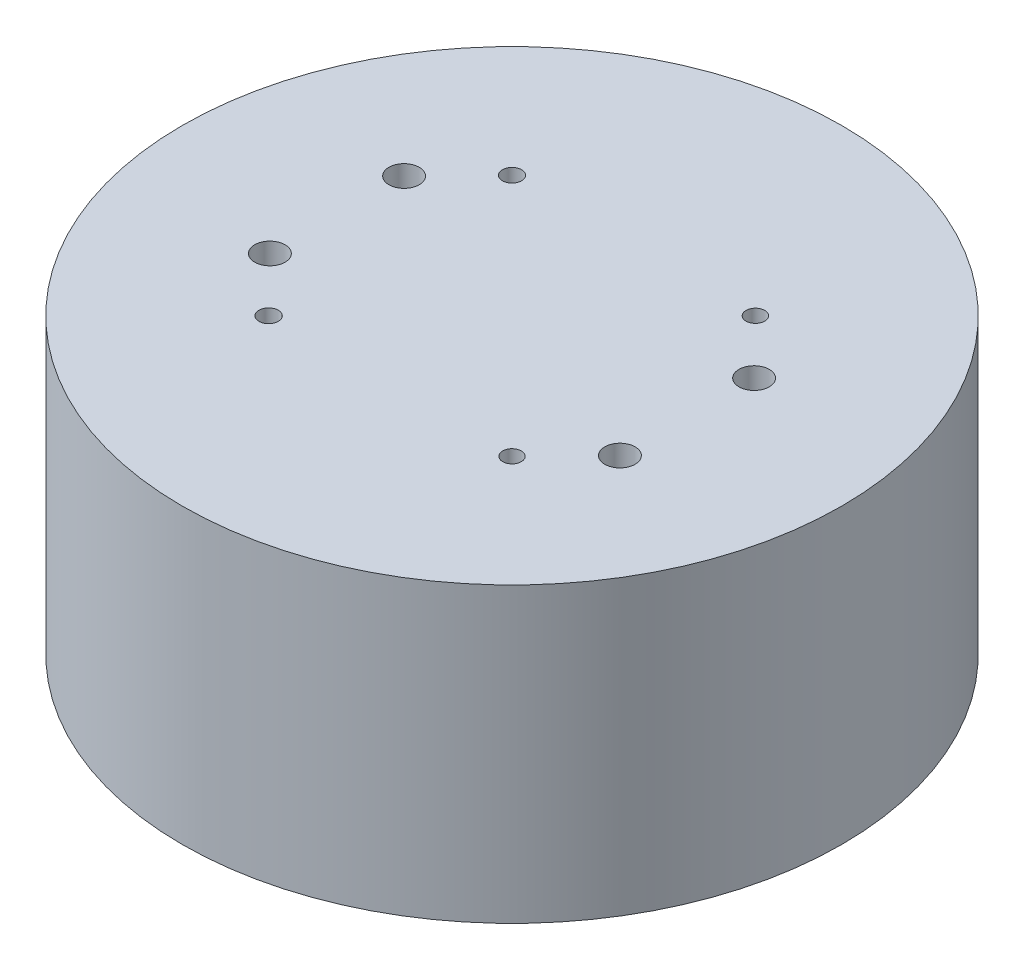
SolidWorks part; units mm, degrees
ref_plane "Front Plane" through (0, 0, 0) normal (0, 0, 1) x (1, 0, 0)
ref_plane "Top Plane" through (0, 0, 0) normal (0, 1, 0) x (1, 0, 0)
ref_plane "Right Plane" through (0, 0, 0) normal (1, 0, 0) x (0, 0, -1)
sketch "Sketch2" plane through (0, 0, 0) normal (0, 1, 0) x (1, 0, 0)
  line L0 (0, 0) -> (0, 56.515)
  circle A0 centre (0, 0) radius 51.435
  circle A1 centre (0, 0) radius 56.515
  circle A2 centre (0, 0) radius 47.2017
  circle A3 centre (0, 0) radius 42.1217
  dimension "D1" = 14.3933
  dimension "D2" = 5.08
  dimension "D3" = 4.2333
  dimension "D4" = 5.08
  dimension "D5" = 102.87
  dimension "D6" = 94.4033
extrude "Boss-Extrude1" add sketch "Sketch2" along normal blind 35 contours A1 A0 | A2 A3
sketch "Sketch3" plane through (0, 35, 0) normal (0, 1, 0) x (1, 0, 0)
  circle A0 centre (0, 0) radius 56.515
  dimension "D1" = 113.03
extrude "Boss-Extrude2" add sketch "Sketch3" along normal blind 15.24
sketch "Sketch4" plane through (0, 50.24, 0) normal (0, 1, 0) x (1, 0, 0)
  line L0 (0, 37.845) -> (0, -37.845) construction
  line L1 (37.845, 0) -> (-37.845, 0) construction
  line L2 (26.7605, 26.7605) -> (-26.7605, -26.7605) construction
  line L3 (-26.7605, 26.7605) -> (26.7605, -26.7605) construction
  circle A0 centre (0, 0) radius 37.845 construction
  circle A1 centre (0, 0) radius 29.5 construction
  circle A2 centre (20.8597, 20.8597) radius 1.6
  circle A3 centre (20.8597, -20.8597) radius 1.6
  circle A4 centre (-20.8597, -20.8597) radius 1.6588
  circle A5 centre (-20.8597, 20.8597) radius 1.651
  point P7 (0, 0)
  point P10 (0, 0)
  point P13 (0, 0)
  point P16 (0, 0)
  dimension "D1" = 75.69
  dimension "D2" = 59
  dimension "D3" = 45
  dimension "D4" = 45
  dimension "D5" = 3.2
  dimension "D6" = 3.2
  dimension "D7" = 3.3175
  dimension "D8" = 3.302
extrude "Cut-Extrude1" cut sketch "Sketch4" against normal through all both and the other way through all
sketch "Sketch5" plane through (0, 0, 0) normal (0, -1, 0) x (-1, 0, 0)
  line L0 (0, 0) -> (0, 29.5)
  line L1 (13.9476, 25) -> (-13.9476, 25)
  circle A1 centre (0, 0) radius 37.845
  circle A2 centre (0, 0) radius 29.5
  arc A3 (-13.9476, 54.7669) -> (13.9476, 54.7669) centre (0, 0) cw
  circle A4 centre (0, 0) radius 56.515 construction
  point P9 (0, 25)
  dimension "D1" = 75.69
  dimension "D2" = 59
  dimension "D3" = 25
  dimension "D4" = 31.515
ref_plane "Plane1" through (0, 0, -56.515) normal (0, 0, 1) x (1, 0, 0)
sketch "Sketch6" plane through (0, 50.24, 0) normal (0, 1, 0) x (1, 0, 0)
  line L0 (0, 0) -> (0, 56.515) construction
  line L1 (0, 0) -> (0, -56.515) construction
  line L2 (-56.515, 0) -> (56.515, 0) construction
  circle A0 centre (0, 0) radius 56.515 construction
  circle A1 centre (0, 30.48) radius 2.6
  circle A2 centre (0, -30.48) radius 2.6
  point P10 (0, 0)
  dimension "D2" = 5.2
  dimension "D3" = 5.2
  dimension "D1" = 113.03
  dimension "D4" = 30.48
  dimension "D5" = 30.48
ref_plane "Plane3" through (0, 0, -47.244) normal (0, 0, 1) x (1, 0, 0)
ref_plane "Plane4" through (17.78, 0, 0) normal (1, 0, 0) x (0, 0, -1)
sketch "Sketch13" plane through (0, 0, -56.515) normal (0, 0, 1) x (1, 0, 0)
  line L0 (0, 0) -> (0, 32.5704) construction
sketch "Sketch14" plane through (0, 0, -56.515) normal (0, 0, 1) x (1, 0, 0)
  line L0 (0, 0) -> (0, 50.24) construction
  line L1 (-56.515, 0) -> (56.515, 0) construction
  line L2 (56.515, 50.24) -> (-56.515, 50.24) construction
  line L3 (0, 20) -> (-5.7214, 20) construction
  line L4 (0, 0) -> (0, 25)
  circle A0 centre (0, 15) radius 10
  dimension "D3" = 20
  dimension "D1" = 10
  dimension "D2" = 25
sketch "Sketch20" plane through (0, 0, 0) normal (0, -1, 0) x (-1, 0, 0)
  circle A0 centre (0, 0) radius 56.515
sketch "Sketch32" plane through (0, 50.24, 0) normal (0, 1, 0) x (1, 0, 0)
  line L0 (0, 56.515) -> (0, -56.515) construction
  line L1 (-56.515, 0) -> (56.515, 0) construction
  line L2 (-30, 0.5) -> (-30, 0) construction
  line L5 (30, 11.5) -> (30, -11.5) construction
  line L6 (-30, 11.5) -> (-30, -11.5) construction
  line L7 (30, 0.5) -> (30, 0) construction
  circle A0 centre (0, 0) radius 56.515 construction
  circle A6 centre (30, 11.5) radius 2.6
  circle A7 centre (30, -11.5) radius 2.6
  circle A8 centre (-30, -11.5) radius 2.6
  circle A9 centre (-30, 11.5) radius 2.6
  point P9 (-28.7356, -11.5)
  point P11 (30, 0)
  point P23 (28.7356, -11.5)
  dimension "D1" = 30
  dimension "D2" = 23
extrude "Cut-Extrude18" cut sketch "Sketch32" against normal up to next
sketch "草图1" plane through (0, 35, 0) normal (0, -1, 0) x (-1, 0, 0)
  circle A0 centre (30, 11.5) radius 6
  circle A1 centre (30, -11.5) radius 6
  circle A2 centre (-30, 11.5) radius 6
  circle A3 centre (-30, -11.5) radius 6
extrude "切除-拉伸1" cut sketch "草图1" against normal blind 5
sketch "草图3" plane through (0, 0, -56.515) normal (0, 0, 1) x (1, 0, 0)
  line L0 (0, 0) -> (0, 35) construction
  circle A0 centre (0, 25) radius 10
  point P5 (0, 0)
  dimension "D1" = 20
  dimension "D2" = 35
  dimension "D3" = 10
extrude "切除-拉伸2" cut sketch "草图3" along normal up to surface (15.5976 mm away)
sketch "草图4" plane through (0, 0, -56.515) normal (0, 0, 1) x (1, 0, 0)
  circle A0 centre (0, 25) radius 10
extrude "拉伸-薄壁1" add sketch "草图4" along normal up to surface (17.1547 mm away) thin
sketch "草图6" plane through (0, 0, -56.515) normal (0, 0, 1) x (1, 0, 0)
  line L0 (-6.6399, 0) -> (6.6399, 0)
  arc A0 (6.6399, 0) -> (-6.6399, 0) centre (0, 25) cw
ref_plane "基准面1" through (13, 0, 0) normal (1, 0, 0) x (0, 0, -1)
ref_plane "基准面2" through (0, 7, 0) normal (0, 1, 0) x (1, 0, 0)
sketch "草图10" plane through (0, 7, 0) normal (0, 1, 0) x (1, 0, 0)
  line L0 (0, 47.2017) -> (0, 51.435)
  line L4 (-15, 44.7549) -> (-15, 49.1992)
  line L5 (-15, 49.1992) -> (-15, 44.7549) construction
  line L10 (15, 44.7549) -> (15, 49.1992)
  circle A0 centre (0, 0) radius 47.2017 construction
  arc A3 (-11.1803, 50.2052) -> (11.1803, 50.2052) centre (0, 0) ccw construction
  arc A4 (15.0893, 49.1719) -> (-15.0893, 49.1719) centre (0, 0) ccw
  arc A5 (15.1117, 44.7173) -> (-15.1117, 44.7173) centre (0, 0) ccw
  dimension "D1" = 0
extrude "拉伸-薄壁3" add sketch "草图10" along normal up to surface (28 mm away) thin
sketch "草图11" plane through (0, 0, 0) normal (0, -1, 0) x (-1, 0, 0)
  circle A0 centre (0, 0) radius 56.515
extrude "切除-拉伸-薄壁3" cut sketch "草图11" against normal up to next thin
sketch "草图12" plane through (0, 7, 0) normal (0, 1, 0) x (1, 0, 0)
  line L0 (15.1244, 44.7549) -> (20, 44.7549)
  line L1 (20, 44.7549) -> (20, 42.7551)
  arc A0 (-15.1117, 44.7173) -> (15.1117, 44.7173) centre (0, 0) ccw construction
  arc A1 (20, 42.7551) -> (15.1117, 44.7173) centre (0, 0) ccw
sketch "草图13" plane through (0, 7, 0) normal (0, 1, 0) x (1, 0, 0)
  line L0 (15.1117, 44.7173) -> (20, 44.7549)
  line L1 (20, 44.7549) -> (15.1244, 44.7549) construction
  line L2 (20, 44.7549) -> (20, 42.7551)
  arc A0 (15.1117, 44.7173) -> (20, 42.7551) centre (0, 0) cw
sketch "草图15" plane through (20, 0, 0) normal (1, 0, 0) x (0, 0, -1)
  line L0 (44.7549, 7) -> (42.2961, 7)
  line L1 (44.7549, 7) -> (44.7549, 35)
  line L2 (44.7549, 35) -> (42.2961, 35)
  line L3 (42.2961, 35) -> (42.2961, 7)
extrude "凸台-拉伸9" add sketch "草图15" against normal blind 5
